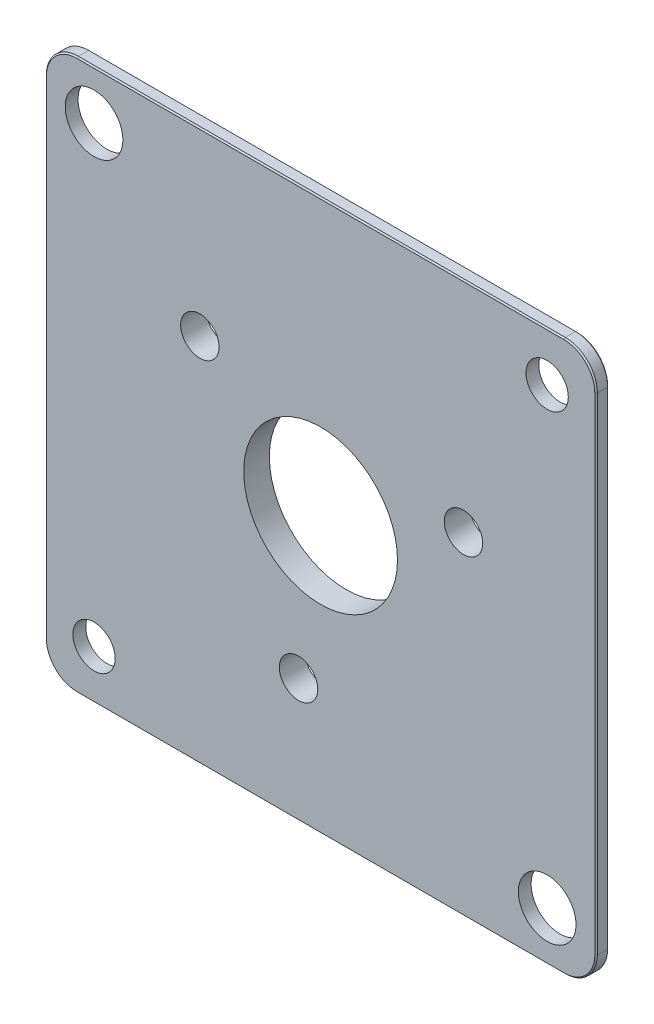
SolidWorks part; units mm, degrees
ref_plane "Front Plane" through (0, 0, 0) normal (0, 0, 1) x (1, 0, 0)
ref_plane "Top Plane" through (0, 0, 0) normal (0, 1, 0) x (1, 0, 0)
ref_plane "Right Plane" through (0, 0, 0) normal (1, 0, 0) x (0, 0, -1)
sketch "Sketch1" plane through (0, 0, 0) normal (0, 0, 1) x (1, 0, 0)
  line L1 (-21.5, -21.5) -> (21.5, -21.5)
  line L2 (-21.5, -21.5) -> (-21.5, 21.5)
  line L3 (-21.5, 21.5) -> (21.5, 21.5)
  line L4 (21.5, -21.5) -> (21.5, 21.5)
  line L5 (-21.5, -21.5) -> (21.5, 21.5) construction
  line L6 (-21.5, 21.5) -> (21.5, -21.5) construction
  circle A0 centre (-17.68, 17.68) radius 2.25
  circle A1 centre (17.68, -17.68) radius 2.25
  circle A2 centre (17.68, 17.68) radius 1.65
  circle A3 centre (-17.68, -17.68) radius 1.65
  point P0 (0, 0)
  dimension "D3" = 3.82
  dimension "D4" = 3.82
  dimension "D5" = 4.5
  dimension "D6" = 3.82
  dimension "D7" = 3.82
  dimension "D8" = 3.3
  dimension "D9" = 4.5
  dimension "D10" = 3.82
  dimension "D11" = 3.82
  dimension "D12" = 3.3
  dimension "D13" = 3.82
  dimension "D1" = 43
  dimension "D2" = 43
extrude "Boss-Extrude1" add sketch "Sketch1" along normal mid plane 1
sketch "Sketch2" plane through (0, 0, 0.5) normal (0, 0, 1) x (1, 0, 0)
  circle A0 centre (0, 0) radius 6
  dimension "D1" = 12
extrude "Cut-Extrude1" cut sketch "Sketch2" against normal blind 1
fillet "Fillet1" radius 2.5 4 edges at (-21.5, -21.5, 0) (21.5, -21.5, 0) (21.5, 21.5, 0) (-21.5, 21.5, 0)
chamfer "Chamfer1" distance 0.1 angle 45 16 edges at (0, -21.5, -0.5) (21.5, 0, -0.5) (20.7678, -20.7678, -0.5) (-20.7678, -20.7678, -0.5) (-21.5, 0, -0.5) (20.7678, 20.7678, -0.5) (-20.7678, 20.7678, -0.5) (0, 21.5, -0.5) (0, 21.5, 0.5) (21.5, 0, 0.5) (0, -21.5, 0.5) (20.7678, 20.7678, 0.5) (20.7678, -20.7678, 0.5) (-20.7678, 20.7678, 0.5) (-20.7678, -20.7678, 0.5) (-21.5, 0, 0.5)
sketch "Sketch3" plane through (0, 0, 0.5) normal (0, 0, 1) x (1, 0, 0)
  line L0 (0, 21.4) -> (0, -21.4)
  line L1 (19, 21.4) -> (-19, 21.4) construction
  line L2 (-19, -21.4) -> (19, -21.4) construction
  line L3 (-21.4, 0) -> (21.5, 0)
  line L4 (-21.4, 19) -> (-21.4, -19) construction
  line L5 (21.5, 19) -> (21.5, -19) construction
  circle A0 centre (11.15, 4.45) radius 1.5
  circle A1 centre (-9.42, 7.43) radius 1.5
  circle A2 centre (-1.72, -11.85) radius 1.5
  dimension "D1" = 9.42
  dimension "D2" = 11.15
  dimension "D3" = 1.72
  dimension "D4" = 4.45
  dimension "D5" = 7.43
  dimension "D6" = 11.85
  dimension "D7" = 3
  dimension "D8" = 3
  dimension "D9" = 3
extrude "Cut-Extrude2" cut sketch "Sketch3" against normal through all contours A1 | A0 | A2
sketch "Sketch4" plane through (0, 0, -0.5) normal (0, 0, -1) x (-1, 0, 0)
  circle A0 centre (0, 0) radius 6
  circle A1 centre (0, 0) radius 16
  circle A2 centre (-11.15, 4.45) radius 1.5
  circle A3 centre (9.42, 7.43) radius 1.5
  circle A4 centre (1.72, -11.85) radius 1.5
  dimension "D1" = 12
  dimension "D2" = 32
extrude "Boss-Extrude2" add sketch "Sketch4" along normal blind 1
